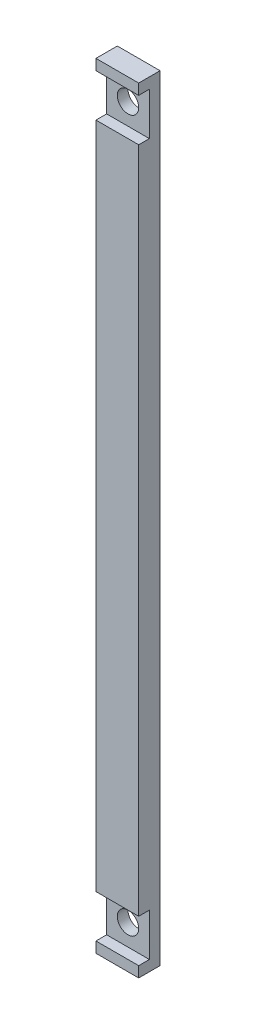
SolidWorks part; units mm, degrees
ref_plane "Front Plane" through (0, 0, 0) normal (0, 0, 1) x (1, 0, 0)
ref_plane "Top Plane" through (0, 0, 0) normal (0, 1, 0) x (1, 0, 0)
ref_plane "Right Plane" through (0, 0, 0) normal (1, 0, 0) x (0, 0, -1)
sketch "Sketch1" plane through (0, 0, 0) normal (0, 1, 0) x (1, 0, 0)
  line L1 (0, 0) -> (25.4, 0)
  line L2 (0, 0) -> (0, 12.7)
  line L3 (0, 12.7) -> (25.4, 12.7)
  line L4 (25.4, 0) -> (25.4, 12.7)
  dimension "D1" = 12.7
  dimension "D2" = 25.4
extrude "Boss-Extrude1" add sketch "Sketch1" along normal blind 460.375
sketch "Sketch2" plane through (25.4, 0, 0) normal (1, 0, 0) x (0, 0, -1)
  line L0 (0, 460.375) -> (0, 0) construction
  line L1 (0, 454.025) -> (6.35, 454.025)
  line L2 (0, 454.025) -> (0, 428.625)
  line L3 (0, 428.625) -> (6.35, 428.625)
  line L4 (6.35, 454.025) -> (6.35, 428.625)
  line L6 (0, 6.35) -> (6.35, 6.35)
  line L7 (0, 6.35) -> (0, 31.75)
  line L8 (0, 31.75) -> (6.35, 31.75)
  line L9 (6.35, 6.35) -> (6.35, 31.75)
  line L11 (0, 460.375) -> (12.7, 460.375) construction
  point P12 (6.35, 460.375)
  dimension "D1" = 6.35
  dimension "D2" = 25.4
  dimension "D3" = 6.35
extrude "Cut-Extrude1" cut sketch "Sketch2" against normal through all
sketch "Sketch3" plane through (0, 0, -6.35) normal (0, 0, 1) x (1, 0, 0)
  line L0 (0, 454.025) -> (25.4, 454.025) construction
  line L1 (25.4, 428.625) -> (25.4, 454.025) construction
  line L2 (25.4, 6.35) -> (25.4, 31.75) construction
  circle A0 centre (12.7, 441.325) radius 6.35
  circle A1 centre (12.7, 19.05) radius 6.35
  point P6 (12.7, 454.025)
  point P9 (25.4, 441.325)
  point P12 (25.4, 19.05)
  dimension "D1" = 12.7
extrude "Cut-Extrude2" cut sketch "Sketch3" against normal through all
equation "\"D3@Sketch2\"=\"D1@Sketch2\""
